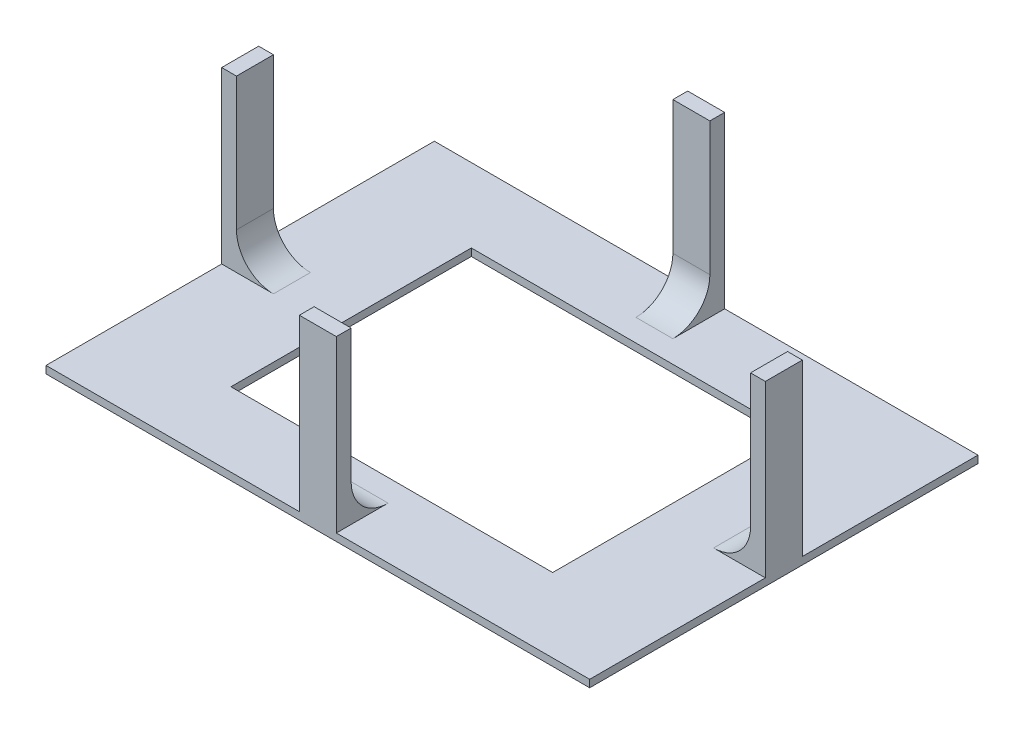
SolidWorks part; units mm, degrees
ref_plane "Alzado" through (0, 0, 0) normal (0, 0, 1) x (1, 0, 0)
ref_plane "Planta" through (0, 0, 0) normal (0, 1, 0) x (1, 0, 0)
ref_plane "Vista lateral" through (0, 0, 0) normal (1, 0, 0) x (0, 0, -1)
sketch "Croquis1" plane through (0, 0, 0) normal (0, 1, 0) x (1, 0, 0)
  line L1 (-36.75, -26.25) -> (36.75, -26.25)
  line L2 (-36.75, -26.25) -> (-36.75, 26.25)
  line L3 (-36.75, 26.25) -> (36.75, 26.25)
  line L4 (36.75, -26.25) -> (36.75, 26.25)
  line L5 (0, 26.25) -> (0, -26.25) construction
  line L6 (-36.75, 0) -> (36.75, 0) construction
  point P0 (0, 0)
  dimension "D1" = 73.5
  dimension "D2" = 52.5
extrude "Saliente-Extruir1" add sketch "Croquis1" along normal blind 24
sketch "Croquis4" plane through (0, 0, 0) normal (0, 1, 0) x (1, 0, 0)
  line L0 (36.75, 26.25) -> (-36.75, 26.25) construction
  line L1 (-34.75, -24.25) -> (34.75, -24.25)
  line L2 (-34.75, -24.25) -> (-34.75, 24.25)
  line L3 (-34.75, 24.25) -> (34.75, 24.25)
  line L4 (34.75, -24.25) -> (34.75, 24.25)
  line L5 (0, 24.25) -> (0, -24.25) construction
  line L6 (-34.75, 0) -> (34.75, 0) construction
  line L7 (-36.75, 26.25) -> (-36.75, -26.25) construction
  point P0 (0, 0)
  dimension "D1" = 2
  dimension "D2" = 2
extrude "Cortar-Extruir1" cut sketch "Croquis4" against normal blind 23 from surface at 24 starting at face at (0, 24, 0)
sketch "Croquis5" plane through (0, 0, 0) normal (0, 1, 0) x (1, 0, 0)
  line L0 (0, 26.25) -> (0, -26.25) construction
  line L1 (36.75, 26.25) -> (-36.75, 26.25) construction
  line L2 (-36.75, -26.25) -> (36.75, -26.25) construction
  line L3 (36.9533, 0) -> (36.75, 0) construction
  line L4 (2.5, 26.25) -> (2.5, 2.5)
  line L5 (36.75, -26.25) -> (36.75, 26.25) construction
  line L6 (36.75, 0) -> (-36.75, 0) construction
  line L7 (-36.75, 26.25) -> (-36.75, -26.25) construction
  line L8 (-36.75, 26.25) -> (-2.5, 26.25)
  line L9 (-36.75, 26.25) -> (-36.75, 2.5)
  line L10 (-36.75, 2.5) -> (-2.5, 2.5)
  line L11 (-2.5, 26.25) -> (-2.5, 2.5)
  line L12 (36.75, 2.5) -> (2.5, 2.5)
  line L13 (36.75, 26.25) -> (36.75, 2.5)
  line L14 (36.75, 26.25) -> (2.5, 26.25)
  line L15 (-36.75, -26.25) -> (-36.75, -2.5)
  line L16 (-36.75, -26.25) -> (-2.5, -26.25)
  line L17 (-2.5, -26.25) -> (-2.5, -2.5)
  line L18 (-36.75, -2.5) -> (-2.5, -2.5)
  line L19 (36.75, -2.5) -> (2.5, -2.5)
  line L20 (36.75, -26.25) -> (36.75, -2.5)
  line L21 (36.75, -26.25) -> (2.5, -26.25)
  line L22 (2.5, -26.25) -> (2.5, -2.5)
  dimension "D1" = 2.5
  dimension "D2" = 2.5
extrude "Cortar-Extruir4" cut sketch "Croquis5" against normal blind 23 from surface at 24 starting at face at (0, 24, 0)
fillet "Redondeo2" radius 5 1 edges at (0, 1, -24.25)
fillet "Redondeo3" radius 5 1 edges at (-34.75, 1, 0)
fillet "Redondeo4" radius 5 1 edges at (0, 1, 24.25)
fillet "Redondeo5" radius 5 1 edges at (34.75, 1, 0)
sketch "Croquis6" plane through (0, 0, 0) normal (0, 1, 0) x (1, 0, 0)
  line L0 (-2.5, 26.25) -> (-36.75, 26.25) construction
  line L1 (-21.75, -16.25) -> (21.75, -16.25)
  line L2 (-21.75, -16.25) -> (-21.75, 16.25)
  line L3 (-21.75, 16.25) -> (21.75, 16.25)
  line L4 (21.75, -16.25) -> (21.75, 16.25)
  line L5 (0, 16.25) -> (0, -16.25) construction
  line L6 (-21.75, 0) -> (21.75, 0) construction
  line L7 (-36.75, 26.25) -> (-36.75, 2.5) construction
  point P0 (0, 0)
  dimension "D1" = 10
  dimension "D2" = 15
extrude "Cortar-Extruir5" cut sketch "Croquis6" against normal through all both and the other way through all
